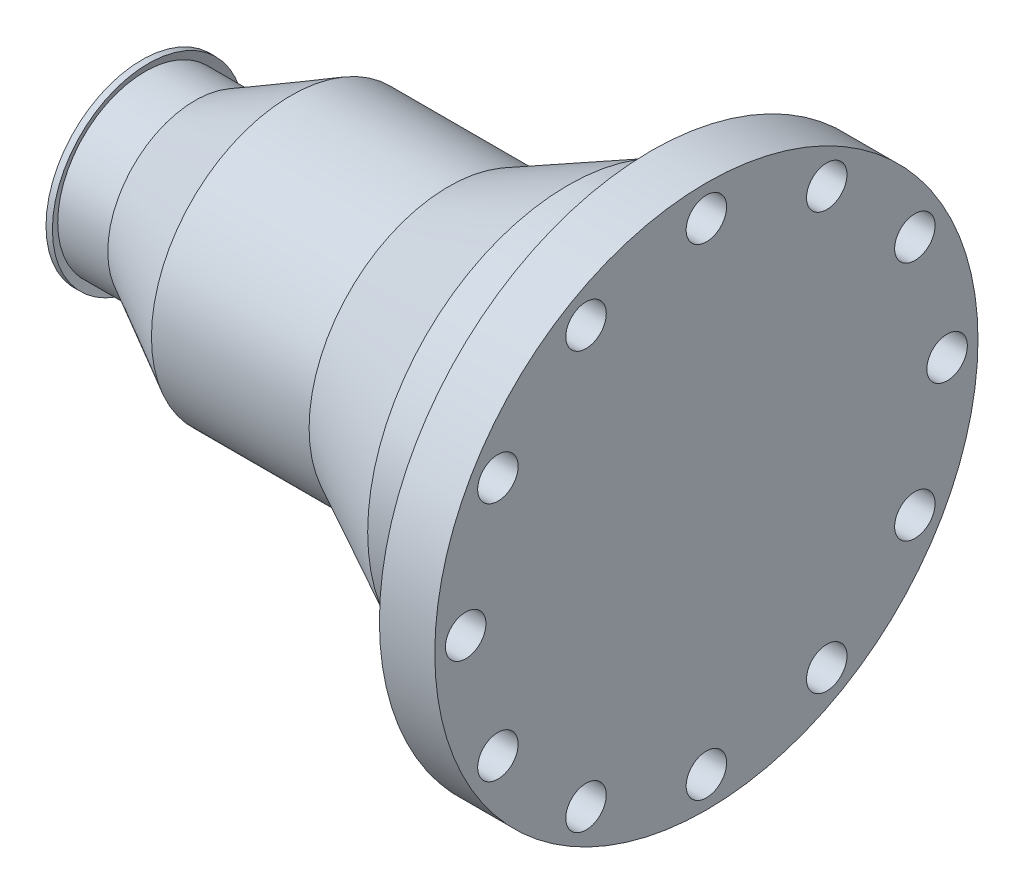
SolidWorks part; units mm, degrees
ref_plane "Спереди" through (0, 0, 0) normal (0, 0, 1) x (1, 0, 0)
ref_plane "Сверху" through (0, 0, 0) normal (0, 1, 0) x (1, 0, 0)
ref_plane "Справа" through (0, 0, 0) normal (1, 0, 0) x (0, 0, -1)
sketch "Эскиз1" plane through (0, 0, 0) normal (0, 0, 1) x (1, 0, 0)
  line L0 (0, 0) -> (265, 0)
  line L1 (0, 0) -> (0, 45)
  line L2 (0, 45) -> (3, 45)
  line L3 (3, 45) -> (1.5, 41)
  line L4 (1.5, 41) -> (25, 41)
  line L5 (25, 41) -> (70, 65.5)
  line L6 (70, 65.5) -> (144, 65.5)
  line L7 (144, 65.5) -> (200, 94)
  line L8 (200, 94) -> (220, 94)
  line L9 (220, 94) -> (220, 95)
  line L10 (220, 95) -> (239, 95)
  line L11 (239, 95) -> (239, 100)
  line L12 (239, 100) -> (239, 127.5)
  line L13 (239, 127.5) -> (265, 127.5)
  line L14 (265, 127.5) -> (265, 0)
revolve "Повернуть1" add sketch "Эскиз1" angle 360 about L0
sketch "Эскиз2" plane through (0, 0, 0) normal (0, 0, 1) x (1, 0, 0)
  line L0 (0, 0) -> (200, 0)
  line L1 (200, 94) -> (200, -94) construction
  line L2 (0, 0) -> (0, 31)
  line L3 (0, 45) -> (0, -45) construction
  line L4 (0, 31) -> (42, 31)
  line L5 (42, 31) -> (70, 38.5026)
  line L6 (70, 65.5) -> (70, -65.5) construction
  line L7 (90, 52.5) -> (95, 52.5)
  line L8 (95, 52.5) -> (177, 52.5)
  line L9 (177, 52.5) -> (187, 52.5)
  line L10 (188.5, 52.5) -> (191.6699, 52.5)
  line L11 (192.6699, 55) -> (200, 55)
  line L12 (200, 55) -> (200, 0)
  arc A0 (70, 38.5026) -> (90, 52.5) centre (107.8022, 5.7765) cw
  arc A1 (187, 52.5) -> (188.5, 52.5) centre (187.75, 49.8032) cw
  arc A2 (191.6699, 52.5) -> (192.6699, 55) centre (192.5934, 53.5806) cw
revolve "Вырез-Повернуть1" cut sketch "Эскиз2" angle 360 about L0
sketch "Эскиз3" plane through (0, 0, 0) normal (1, 0, 0) x (0, 0, -1)
  circle A0 centre (0, 113) radius 9.5
extrude "Вырез-Вытянуть1" cut sketch "Эскиз3" along normal through all
sketch "Эскиз4" plane through (0, 0, 0) normal (1, 0, 0) x (0, 0, -1)
  circle A0 centre (-56.5, 97.8609) radius 9.5
extrude "Вырез-Вытянуть2" cut sketch "Эскиз4" along normal through all
sketch "Эскиз5" plane through (0, 0, 0) normal (1, 0, 0) x (0, 0, -1)
  circle A0 centre (-97.8609, 56.5) radius 9.5
extrude "Вырез-Вытянуть3" cut sketch "Эскиз5" along normal through all
sketch "Эскиз6" plane through (0, 0, 0) normal (1, 0, 0) x (0, 0, -1)
  circle A0 centre (-113, 0) radius 9.5
extrude "Вырез-Вытянуть4" cut sketch "Эскиз6" along normal through all
sketch "Эскиз7" plane through (0, 0, 0) normal (1, 0, 0) x (0, 0, -1)
  circle A0 centre (-97.8609, -56.5) radius 9.5
extrude "Вырез-Вытянуть5" cut sketch "Эскиз7" along normal through all
sketch "Эскиз8" plane through (0, 0, 0) normal (1, 0, 0) x (0, 0, -1)
  circle A0 centre (-56.5, -97.8609) radius 9.5
extrude "Вырез-Вытянуть6" cut sketch "Эскиз8" along normal through all
sketch "Эскиз9" plane through (0, 0, 0) normal (1, 0, 0) x (0, 0, -1)
  circle A0 centre (0, -113) radius 9.5
extrude "Вырез-Вытянуть7" cut sketch "Эскиз9" along normal through all
sketch "Эскиз10" plane through (0, 0, 0) normal (1, 0, 0) x (0, 0, -1)
  circle A0 centre (56.5, -97.8609) radius 9.5
extrude "Вырез-Вытянуть8" cut sketch "Эскиз10" along normal through all
sketch "Эскиз11" plane through (0, 0, 0) normal (1, 0, 0) x (0, 0, -1)
  circle A0 centre (97.8609, -56.5) radius 9.5
extrude "Вырез-Вытянуть9" cut sketch "Эскиз11" along normal through all
sketch "Эскиз12" plane through (0, 0, 0) normal (1, 0, 0) x (0, 0, -1)
  circle A0 centre (113, 0) radius 9.5
extrude "Вырез-Вытянуть10" cut sketch "Эскиз12" along normal through all
sketch "Эскиз13" plane through (0, 0, 0) normal (1, 0, 0) x (0, 0, -1)
  circle A0 centre (97.8609, 56.5) radius 9.5
extrude "Вырез-Вытянуть11" cut sketch "Эскиз13" along normal through all
sketch "Эскиз14" plane through (0, 0, 0) normal (1, 0, 0) x (0, 0, -1)
  circle A0 centre (56.5, 97.8609) radius 9.5
extrude "Вырез-Вытянуть12" cut sketch "Эскиз14" along normal through all
